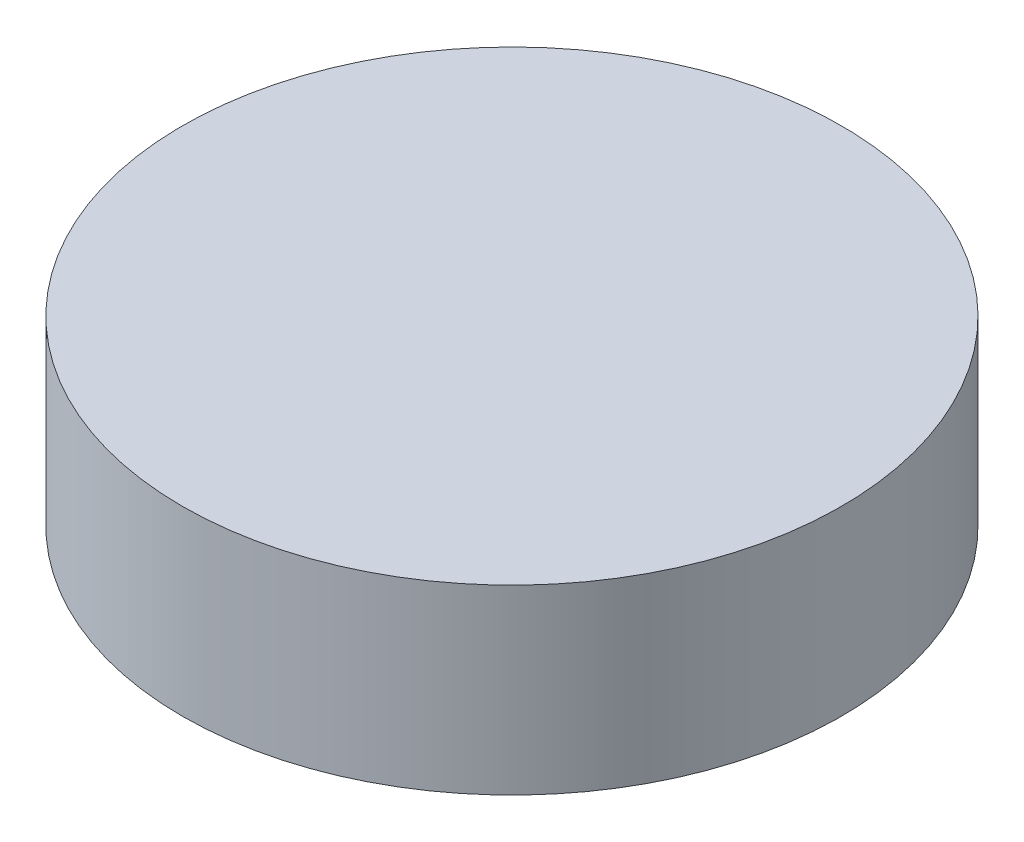
SolidWorks part; units mm, degrees
ref_plane "Front Plane" through (0, 0, 0) normal (0, 0, 1) x (1, 0, 0)
ref_plane "Top Plane" through (0, 0, 0) normal (0, 1, 0) x (1, 0, 0)
ref_plane "Right Plane" through (0, 0, 0) normal (1, 0, 0) x (0, 0, -1)
sketch "Sketch1" plane through (0, 0, 0) normal (0, 1, 0) x (1, 0, 0)
  circle A0 centre (0, 0) radius 10.605
  dimension "D1" = 21.21
extrude "Boss-Extrude1" add sketch "Sketch1" along normal blind 5.85
